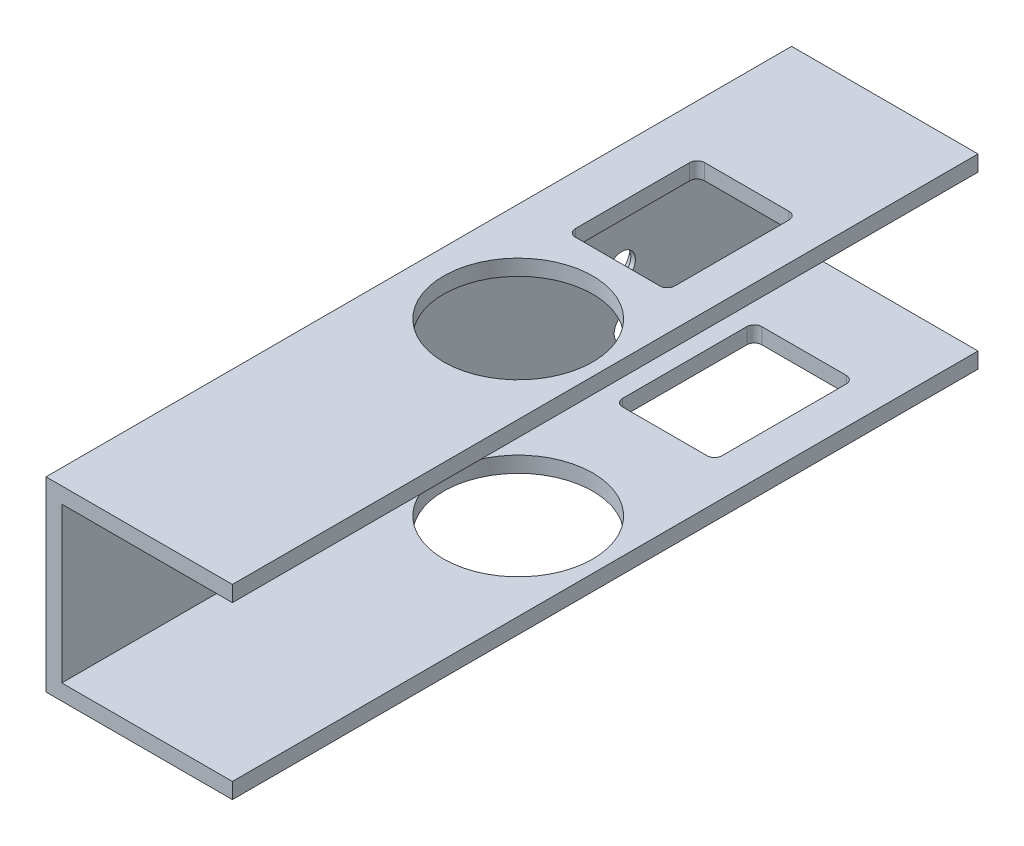
SolidWorks part; units mm, degrees
ref_plane "Front Plane" through (0, 0, 0) normal (0, 0, 1) x (1, 0, 0)
ref_plane "Top Plane" through (0, 0, 0) normal (0, 1, 0) x (1, 0, 0)
ref_plane "Right Plane" through (0, 0, 0) normal (1, 0, 0) x (0, 0, -1)
sketch "Sketch1" plane through (0, 0, 0) normal (0, 0, 1) x (1, 0, 0)
  line L0 (0, -37.5) -> (0, 37.5)
  line L1 (0, 37.5) -> (75, 37.5)
  line L2 (75, 37.5) -> (75, 31.15)
  line L3 (75, 31.15) -> (6.35, 31.15)
  line L4 (6.35, 31.15) -> (6.35, -31.15)
  line L5 (6.35, -31.15) -> (75, -31.15)
  line L6 (75, -31.15) -> (75, -37.5)
  line L7 (75, -37.5) -> (0, -37.5)
  line L8 (0, 0) -> (6.35, 0) construction
  dimension "D1" = 75
  dimension "D2" = 75
  dimension "D3" = 6.35
extrude "Boss-Extrude1" add sketch "Sketch1" along normal blind 300
sketch "Sketch2" plane through (0, 37.5, 0) normal (0, 1, 0) x (1, 0, 0)
  line L0 (0, -300) -> (0, 0) construction
  line L1 (75, -300) -> (0, -300) construction
  circle A0 centre (40, -150) radius 30
  dimension "D1" = 60
  dimension "D2" = 40
  dimension "D3" = 150
extrude "Cut-Extrude1" cut sketch "Sketch2" against normal through all
sketch "Sketch3" plane through (0, -37.5, 0) normal (0, -1, 0) x (1, 0, 0)
  line L0 (20, 91) -> (20, 35)
  line L1 (20, 91) -> (60, 91)
  line L2 (20, 35) -> (60, 35)
  line L3 (60, 91) -> (60, 35)
  line L4 (20, 91) -> (60, 35) construction
  line L5 (20, 35) -> (60, 91) construction
  line L6 (40, 91) -> (40, 150) construction
  circle A0 centre (40, 150) radius 30 construction
  point P1 (40, 63)
  dimension "D1" = 59
  dimension "D2" = 40
  dimension "D3" = 56
extrude "Cut-Extrude2" cut sketch "Sketch3" against normal blind 10
sketch "Sketch4" plane through (0, 37.5, 0) normal (0, 1, 0) x (1, 0, 0)
  line L0 (60, -110) -> (60, -58)
  line L1 (60, -110) -> (20, -110)
  line L2 (60, -58) -> (20, -58)
  line L3 (20, -110) -> (20, -58)
  line L4 (60, -110) -> (20, -58) construction
  line L5 (60, -58) -> (20, -110) construction
  line L6 (40, -110) -> (40, -150) construction
  circle A0 centre (40, -150) radius 30 construction
  point P1 (40, -84)
  dimension "D1" = 92
  dimension "D2" = 40
  dimension "D3" = 40
extrude "Cut-Extrude3" cut sketch "Sketch4" against normal blind 10
fillet "Fillet1" radius 3 8 edges at (60, -34.325, 35) (60, -34.325, 91) (20, -34.325, 91) (20, -34.325, 35) (60, 34.325, 110) (60, 34.325, 58) (20, 34.325, 58) (20, 34.325, 110)
hole_wizard "CSK for M10 Countersunk Flat Head Screw1" positions "Sketch6" profile "Sketch5" countersink size "M10" standard "ISO"
sketch "Sketch6" plane through (0, 0, 0) normal (-1, 0, 0) x (0, 0, 1)
  point P0 (74.7041, 1.0111)
  point P5 (72.25, -20.6)
  point P13 (79.836, 23.1884)
  dimension "D1" = 21.6111
sketch "Sketch5" plane through (0, 1.0111, 74.7041) normal (0, 1, 0) x (0, 0, 1)
  line L0 (0, 0) -> (0, 23.3077)
  line L1 (0, 23.3077) -> (5.5, 20.003)
  line L2 (5.5, 20.003) -> (5.5, 4.5)
  line L3 (5.5, 4.5) -> (10, 0)
  line L5 (10, 0) -> (0, 0)
  line L6 (-5.5, 4.5) -> (-10, 0) construction
  line L10 (0, 23.3077) -> (-5.5, 20.003) construction
  line L11 (0, -6.35) -> (0, 107.95) construction
  dimension "Hole Dia." = 11
  dimension "Hole Depth" = 20.003
  dimension "Near C'Sink Dia." = 20
  dimension "Near C'Sink Angle" = 90
  dimension "Drill Angle" = 118
